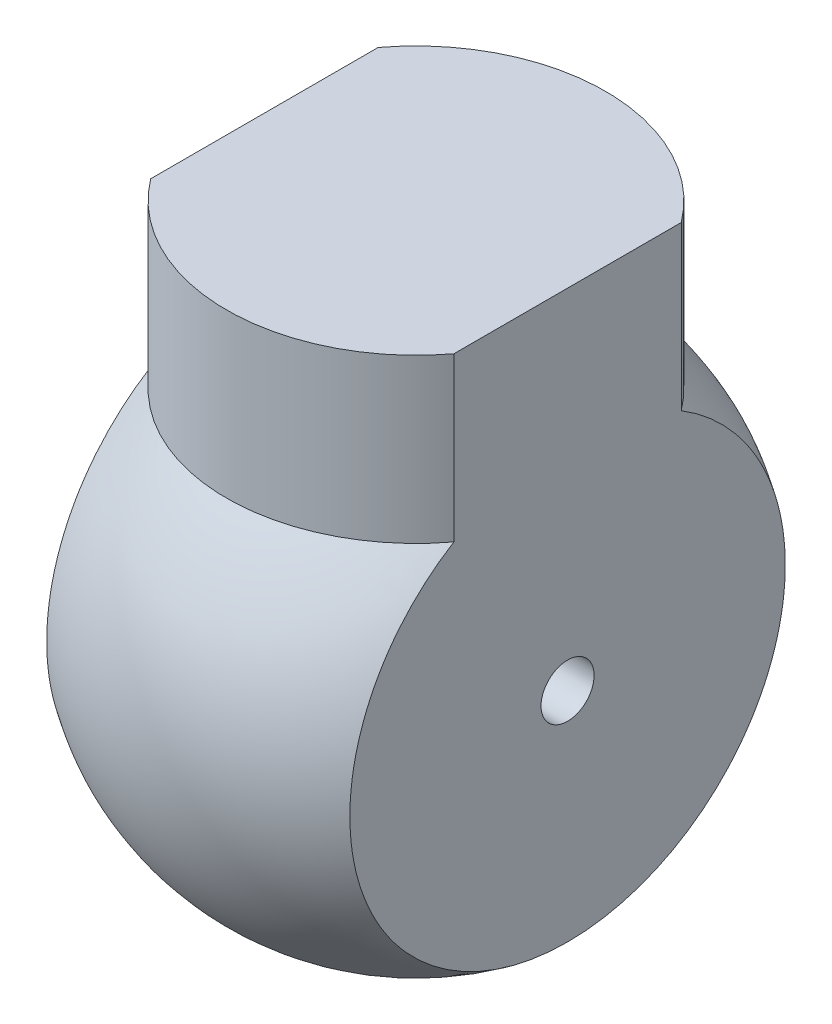
SolidWorks part; units mm, degrees
ref_plane "Front Plane" through (0, 0, 0) normal (0, 0, 1) x (1, 0, 0)
ref_plane "Top Plane" through (0, 0, 0) normal (0, 1, 0) x (1, 0, 0)
ref_plane "Right Plane" through (0, 0, 0) normal (1, 0, 0) x (0, 0, -1)
sketch "Sketch1" plane through (0, 0, 0) normal (0, 1, 0) x (1, 0, 0)
  line L0 (0, 35) -> (0, -35) construction
  line L1 (0, 35) -> (0, -35)
  arc A0 (0, -35) -> (0, 35) centre (0, 0) ccw
  dimension "D1" = 70
revolve "Revolve2" add sketch "Sketch1" angle 360 about L0
sketch "Sketch2" plane through (0, 0, 0) normal (0, 1, 0) x (1, 0, 0)
  line L2 (-20, -28.7228) -> (-20, 28.7228)
  line L4 (20, -28.7228) -> (20, 28.7228)
  line L5 (-20, -35) -> (20, 35) construction
  line L6 (-20, 35) -> (20, -35) construction
  arc A0 (20, 28.7228) -> (-20, 28.7228) centre (0, 0) ccw
  arc A1 (-20, -28.7228) -> (20, -28.7228) centre (0, 0) ccw
  dimension "D1" = 40
extrude "Cut-Extrude1" cut sketch "Sketch2" against normal up to next and the other way up to next flip side to cut
sketch "Sketch3" plane through (0, 0, 0) normal (0, 1, 0) x (1, 0, 0)
  line L4 (20, -28.7228) -> (20, 28.7228) construction
  line L6 (-20, 15) -> (-20, -15)
  line L8 (20, 15) -> (20, -15)
  line L9 (-20, 26.2775) -> (20, -26.2775) construction
  line L10 (-20, -26.2775) -> (20, 26.2775) construction
  arc A3 (20, 15) -> (-20, 15) centre (0, 0) ccw
  arc A4 (-20, -15) -> (20, -15) centre (0, 0) ccw
  arc A6 (-20, -28.7228) -> (20, -28.7228) centre (0, 0) ccw construction
  dimension "D1" = 50
  dimension "D2" = 10
extrude "Boss-Extrude1" add sketch "Sketch3" along normal blind 46
sketch "Sketch4" plane through (-20, 0, 0) normal (-1, 0, 0) x (0, 0, 1)
  circle A0 centre (0, 0) radius 3.5
  dimension "D1" = 7
extrude "Cut-Extrude2" cut sketch "Sketch4" against normal blind 5
pattern_linear "LPattern1" count 2 spacing 35 along (1, 0, 0) of "Cut-Extrude2"
scale "Scale1" scale about centroid uniform scaling yes scale factor 0.2286
